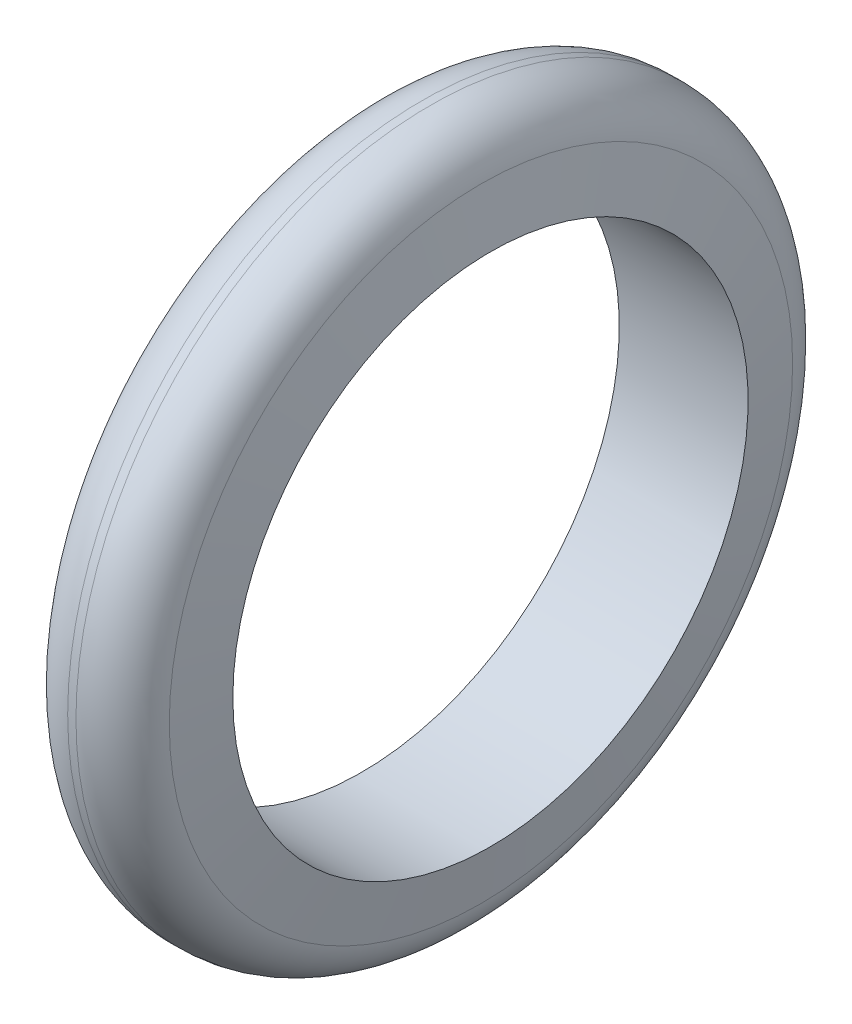
SolidWorks part; units mm, degrees
ref_plane "Front Plane" through (0, 0, 0) normal (0, 0, 1) x (1, 0, 0)
ref_plane "Top Plane" through (0, 0, 0) normal (0, 1, 0) x (1, 0, 0)
ref_plane "Right Plane" through (0, 0, 0) normal (1, 0, 0) x (0, 0, -1)
sketch "Sketch1" plane through (0, 0, 0) normal (0, 0, 1) x (1, 0, 0)
  line L0 (0, 0) -> (62.1539, 0) construction
  line L1 (0, 0) -> (0, 48.643) construction
  line L3 (-7.3551, 55) -> (7.3551, 55)
  line L4 (-7.3551, 55) -> (-10, 40)
  line L5 (-10, 40) -> (10, 40)
  line L6 (7.3551, 55) -> (10, 40)
  line L7 (-7.3551, 55) -> (10, 40) construction
  line L8 (-10, 40) -> (7.3551, 55) construction
  dimension "D1" = 80
  dimension "D2" = 110
  dimension "D3" = 10
  dimension "D4" = 20
revolve "Revolve1" add sketch "Sketch1" angle 360 about L0
fillet "Fillet1" radius 8 2 edges at (7.3551, 0, 55) (-7.3551, 0, 55)
